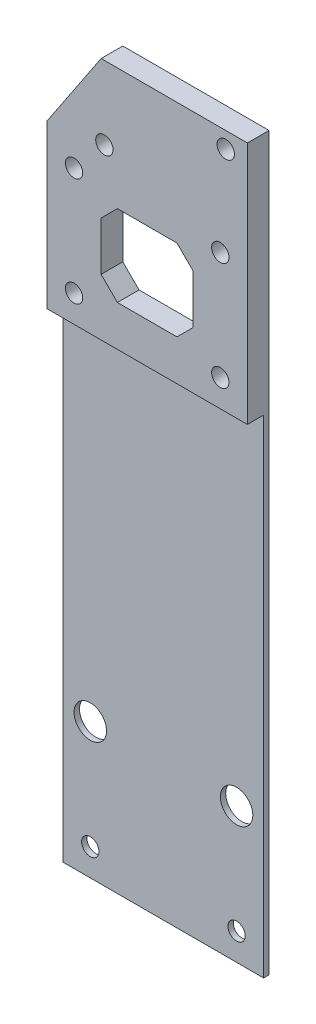
SolidWorks part; units mm, degrees
ref_plane "正面" through (0, 0, 0) normal (0, 0, 1) x (1, 0, 0)
ref_plane "平面" through (0, 0, 0) normal (0, 1, 0) x (1, 0, 0)
ref_plane "右側面" through (0, 0, 0) normal (1, 0, 0) x (0, 0, -1)
sketch "ｽｹｯﾁ1" plane through (0, 0, 0) normal (0, 0, 1) x (1, 0, 0)
  line L1 (-18.5, -60) -> (18.5, -60)
  line L2 (-18.5, -60) -> (-18.5, 60)
  line L3 (-18.5, 60) -> (18.5, 60)
  line L4 (18.5, -60) -> (18.5, 60)
  line L5 (-18.5, -60) -> (18.5, 60) construction
  line L6 (-18.5, 60) -> (18.5, -60) construction
  line L8 (-18.5, 25) -> (-18.5, -25)
  circle A0 centre (-13.5, 55) radius 1.6
  circle A1 centre (-13.5, 35) radius 1.6
  circle A2 centre (13.5, 55) radius 1.6
  circle A3 centre (13.5, 35) radius 1.6
  circle A4 centre (-13.5, -35) radius 3
  circle A5 centre (-13.5, -55) radius 1.6
  circle A6 centre (13.5, -35) radius 3
  circle A7 centre (13.5, -55) radius 1.6
  point P0 (0, 0)
  dimension "D3" = 3.2
  dimension "D4" = 3.2
  dimension "D5" = 3.2
  dimension "D6" = 3.2
  dimension "D7" = 6
  dimension "D8" = 3.2
  dimension "D9" = 6
  dimension "D10" = 3.2
  dimension "D11" = 5
  dimension "D12" = 5
  dimension "D13" = 5
  dimension "D14" = 5
  dimension "D15" = 20
  dimension "D16" = 5
  dimension "D17" = 5
  dimension "D18" = 20
  dimension "D19" = 20
  dimension "D20" = 5
  dimension "D21" = 5
  dimension "D22" = 20
  dimension "D23" = 5
  dimension "D24" = 5
  dimension "D25" = 20
  dimension "D26" = 5
  dimension "D27" = 5
  dimension "D1" = 120
  dimension "D2" = 37
extrude "ﾎﾞｽ - 押し出し1" add sketch "ｽｹｯﾁ1" along normal blind 4
sketch "ｽｹｯﾁ2" plane through (0, 0, 4) normal (0, 0, 1) x (1, 0, 0)
  line L0 (18.5, -60) -> (18.5, 60) construction
  line L1 (-18.5, -60) -> (18.5, -60)
  line L2 (-18.5, -60) -> (-18.5, 30)
  line L3 (-18.5, 30) -> (18.5, 30)
  line L4 (18.5, -60) -> (18.5, 30)
  line L5 (-18.5, 60) -> (18.5, 60) construction
  dimension "D1" = 30
extrude "ｶｯﾄ - 押し出し1" cut sketch "ｽｹｯﾁ2" against normal blind 3
sketch "ｽｹｯﾁ3" plane through (0, 0, 0) normal (0, 0, -1) x (-1, 0, 0)
  line L0 (-18.5, -60) -> (-18.5, 60) construction
  line L1 (-8.5, 52.5) -> (8.5, 52.5)
  line L2 (-8.5, 52.5) -> (-8.5, 37.5)
  line L3 (-8.5, 37.5) -> (8.5, 37.5)
  line L4 (8.5, 52.5) -> (8.5, 37.5)
  line L5 (18.5, -60) -> (18.5, 60) construction
  line L6 (18.5, 60) -> (-18.5, 60) construction
  point P10 (8.5, 45)
  dimension "D1" = 10
  dimension "D2" = 10
  dimension "D3" = 15
  dimension "D4" = 15
extrude "ｶｯﾄ - 押し出し2" cut sketch "ｽｹｯﾁ3" against normal through all
chamfer "面取り1" distance 3 angle 45 4 edges at (-8.5, 37.5, 2) (8.5, 37.5, 2) (8.5, 52.5, 2) (-8.5, 52.5, 2)
sketch "ｽｹｯﾁ4" plane through (0, 0, 4) normal (0, 0, 1) x (1, 0, 0)
  line L0 (-18.5, 60) -> (-8.5, 75)
  line L1 (-8.5, 75) -> (18.5, 75)
  line L2 (18.5, 75) -> (18.5, 60)
  line L3 (-18.5, 60) -> (18.5, 60) construction
  line L4 (-18.5, 60) -> (18.5, 60)
  line L8 (-18.5, 30) -> (18.5, 30)
  line L9 (18.5, 30) -> (18.5, 60)
  line L10 (18.5, 60) -> (-18.5, 60)
  line L11 (-18.5, 60) -> (-18.5, 30)
  line L12 (-18.5, 30) -> (18.5, 30)
  line L13 (18.5, 30) -> (18.5, 60)
  line L15 (-18.5, 60) -> (-18.5, 30)
  line M16 (18.5, 60) -> (-18.5, 60)
  dimension "D1" = 15
  dimension "D2" = 10
  dimension "D3" = 0
  dimension "D4" = 0
extrude "ﾎﾞｽ - 押し出し2" add sketch "ｽｹｯﾁ4" against normal through all contours L2 L1 L0 M16
sketch "ｽｹｯﾁ5" plane through (0, 0, 4) normal (0, 0, 1) x (1, 0, 0)
  line L0 (-8.5, 75) -> (18.5, 75) construction
  line L1 (18.5, 30) -> (18.5, 75) construction
  circle A0 centre (14.5, 72) radius 1.6
  circle A1 centre (-7.9, 61.5) radius 1.6
  dimension "D1" = 3.2
  dimension "D3" = 4
  dimension "D4" = 26.4
  dimension "D5" = 3.2
  dimension "D6" = 10.5
  dimension "D2" = 3
extrude "ｶｯﾄ - 押し出し3" cut sketch "ｽｹｯﾁ5" against normal through all
